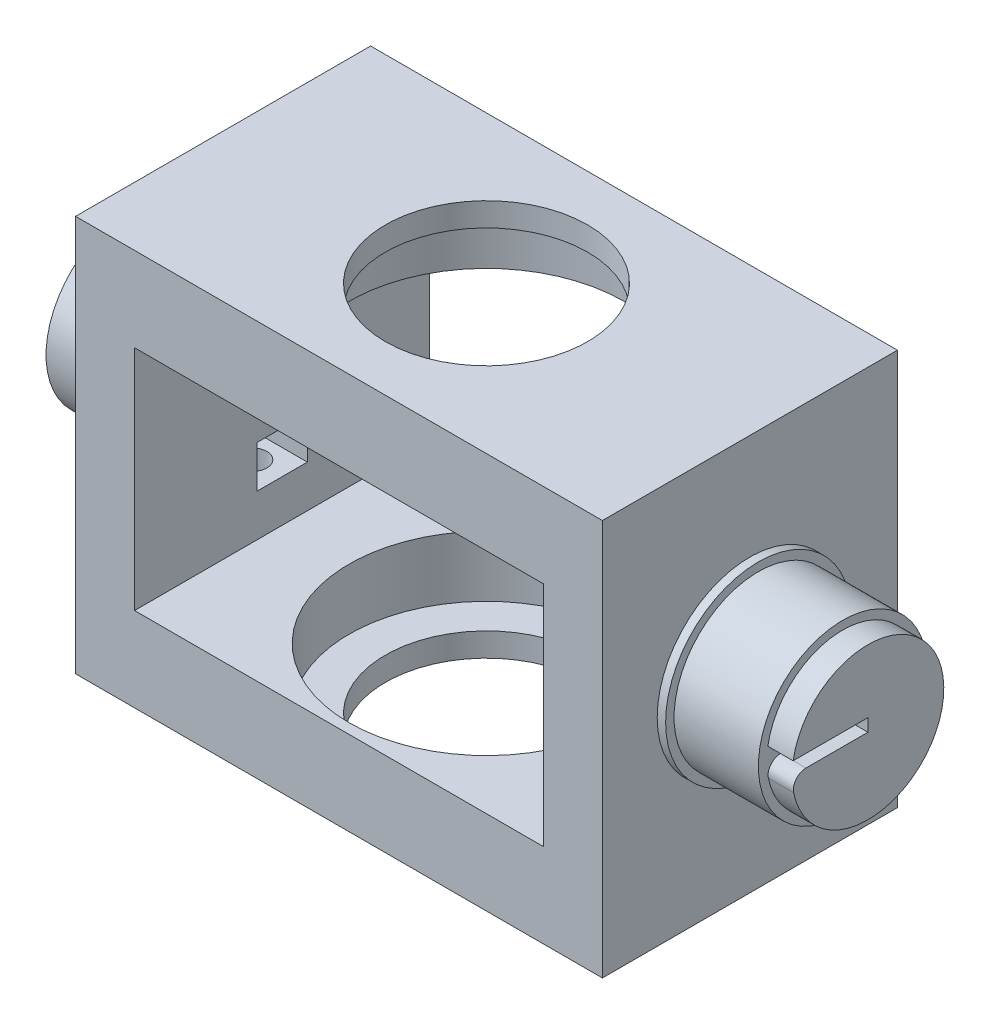
SolidWorks part; units mm, degrees
ref_plane "前视基准面" through (0, 0, 0) normal (0, 0, 1) x (1, 0, 0)
ref_plane "上视基准面" through (0, 0, 0) normal (0, 1, 0) x (1, 0, 0)
ref_plane "右视基准面" through (0, 0, 0) normal (1, 0, 0) x (0, 0, -1)
sketch "草图1" plane through (0, 0, 0) normal (0, 1, 0) x (1, 0, 0)
  line L1 (-31.25, -17.5) -> (31.25, -17.5)
  line L2 (-31.25, -17.5) -> (-31.25, 17.5)
  line L3 (-31.25, 17.5) -> (31.25, 17.5)
  line L4 (31.25, -17.5) -> (31.25, 17.5)
  circle A0 centre (0, 0) radius 12
  dimension "D5" = 24
  dimension "D1" = 35
  dimension "D2" = 62.5
  dimension "D3" = 31.25
  dimension "D4" = 17.5
extrude "凸台-拉伸1" add sketch "草图1" along normal blind 10
ref_plane "基准面1" through (0, 10, 0) normal (0, 1, 0) x (1, 0, 0)
sketch "草图2" plane through (0, 10, 0) normal (0, 1, 0) x (1, 0, 0)
  circle A0 centre (0, 0) radius 16.3
  dimension "D1" = 32.6
extrude "切除-拉伸1" cut sketch "草图2" against normal blind 7.2
sketch "草图4" plane through (0, 0, 0) normal (0, 1, 0) x (1, 0, 0)
  line L0 (31.25, 17.5) -> (-31.25, 17.5) construction
  line L1 (31.25, -17.5) -> (24.25, -17.5)
  line L2 (31.25, -17.5) -> (31.25, 17.5)
  line L3 (31.25, 17.5) -> (24.25, 17.5)
  line L4 (24.25, -17.5) -> (24.25, 17.5)
  dimension "D1" = 7
extrude "凸台-拉伸3" add sketch "草图4" along normal blind 37
sketch "草图5" plane through (0, 0, 0) normal (0, 1, 0) x (1, 0, 0)
  line L0 (31.25, 0) -> (27.75, 0)
  line L1 (31.25, -17.5) -> (31.25, 17.5) construction
  circle A0 centre (27.75, 0) radius 3
  dimension "D2" = 6
  dimension "D1" = 3.5
extrude "切除-拉伸3" cut sketch "草图5" along normal blind 3
sketch "草图7" plane through (0, 0, 0) normal (0, 1, 0) x (1, 0, 0)
  circle A0 centre (27.75, 0) radius 1.7
  dimension "D1" = 3.4
extrude "切除-拉伸4" cut sketch "草图7" along normal blind 20 contours A0
ref_plane "基准面2" through (31.25, 0, 0) normal (1, 0, 0) x (0, 0, -1)
sketch "草图9" plane through (31.25, 0, 0) normal (1, 0, 0) x (0, 0, -1)
  line L0 (0, 0) -> (0, 20) construction
  line L1 (-17.5, 0) -> (17.5, 0) construction
  line L3 (-3, 20) -> (3, 20)
  line L4 (-3, 20) -> (-3, 15)
  line L5 (-3, 15) -> (3, 15)
  line L6 (3, 20) -> (3, 15)
  dimension "D1" = 20
  dimension "D2" = 6
  dimension "D3" = 5
  dimension "D4" = 3
extrude "切除-拉伸5" cut sketch "草图9" against normal blind 7
ref_plane "基准面3" through (0, 0, 0) normal (-1, 0, 0) x (0, 0, 1)
ref_plane "基准面4" through (0, 23.5, 0) normal (0, 1, 0) x (1, 0, 0)
mirror "镜向4" about plane through (0, 0, 0) normal (-1, 0, 0) of "切除-拉伸5", "凸台-拉伸3", "切除-拉伸3", "切除-拉伸4"
mirror "镜向5" about plane through (0, 23.5, 0) normal (0, 1, 0) of "切除-拉伸1", "凸台-拉伸1"
sketch "草图10" plane through (31.25, 0, 0) normal (1, 0, 0) x (0, 0, -1)
  line L0 (-17.5, 23.5) -> (17.5, 23.5) construction
  line L1 (-17.5, 47) -> (-17.5, 0) construction
  line L2 (17.5, 47) -> (17.5, 0) construction
  circle A0 centre (0, 23.5) radius 10
  dimension "D1" = 20
extrude "凸台-拉伸4" add sketch "草图10" along normal blind 11
sketch "草图11" plane through (31.25, 0, 0) normal (1, 0, 0) x (0, 0, -1)
  circle A0 centre (0, 23.5) radius 11
  dimension "D1" = 22
extrude "凸台-拉伸5" add sketch "草图11" along normal blind 1
mirror "镜向6" about plane through (0, 0, 0) normal (-1, 0, 0) of "凸台-拉伸4", "凸台-拉伸5"
ref_plane "基准面5" through (42.25, 0, 0) normal (1, 0, 0) x (0, 0, -1)
sketch "草图12" plane through (42.25, 0, 0) normal (1, 0, 0) x (0, 0, -1)
  line L0 (0, 23.5) -> (-7.3485, 23.5)
  line L2 (-8.8741, 25) -> (0, 25)
  line L3 (0, 25) -> (0, 23.5)
  arc A0 (-8.8182, 21.7) -> (-8.8741, 25) centre (0, 23.5) ccw
  arc A1 (-7.3485, 23.5) -> (-8.8182, 21.7) centre (-7.3485, 22) ccw
  dimension "D1" = 18
  dimension "D3" = 1.5
  dimension "D2" = 1.5
extrude "凸台-拉伸6" add sketch "草图12" along normal blind 3
ref_plane "基准面6" through (-42.25, 0, 0) normal (-1, 0, 0) x (0, 0, 1)
sketch "草图13" plane through (-42.25, 0, 0) normal (-1, 0, 0) x (0, 0, 1)
  line L1 (-1.5612, 24.75) -> (1.5612, 24.75)
  line L3 (-1.5612, 22.25) -> (1.5612, 22.25)
  arc A0 (1.5612, 22.25) -> (1.5612, 24.75) centre (0, 23.5) ccw
  arc A1 (-1.5612, 24.75) -> (-1.5612, 22.25) centre (0, 23.5) ccw
  dimension "D1" = 4
  dimension "D2" = 1.25
  dimension "D4" = 1.25
extrude "切除-拉伸6" cut sketch "草图13" against normal blind 5.5
sketch "草图14" plane through (0, 0, 0) normal (0, 1, 0) x (1, 0, 0)
  line L1 (31.25, -17.5) -> (-31.25, -17.5)
  line L2 (31.25, -17.5) -> (31.25, 17.5)
  line L3 (31.25, 17.5) -> (-31.25, 17.5)
  line L4 (-31.25, -17.5) -> (-31.25, 17.5)
sketch "草图16" plane through (0, 10, 0) normal (0, 1, 0) x (1, 0, 0)
  line L0 (24.25, 17.5) -> (-24.25, 17.5) construction
  line L5 (-47.224, -22.5818) -> (46.8453, -22.5818)
  line L6 (-47.224, -22.5818) -> (-47.224, 25.8512)
  line L7 (-47.224, 25.8512) -> (46.8453, 25.8512)
  line L8 (46.8453, -22.5818) -> (46.8453, 25.8512)
  dimension "D1" = 94.0693
  dimension "D2" = 48.433
  dimension "D3" = 8.3512
  dimension "D4" = 15.974
sketch "草图18" plane through (0, 10, 0) normal (0, 1, 0) x (1, 0, 0)
  line L0 (24.25, 17.5) -> (-24.25, 17.5) construction
  line L1 (-31.25, -17.5) -> (-23.95, -17.5)
  line L2 (-31.25, -17.5) -> (-31.25, 17.5)
  line L3 (-31.25, 17.5) -> (-23.95, 17.5)
  line L4 (-23.95, -17.5) -> (-23.95, 17.5)
  dimension "D1" = 7.3
